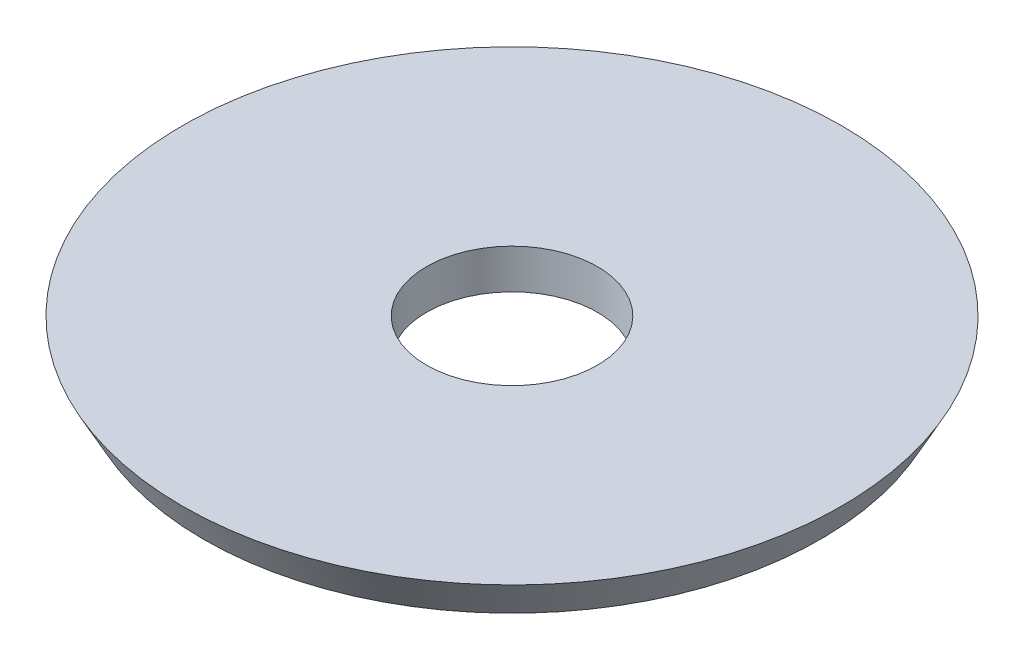
SolidWorks part; units mm, degrees
material "Epoxy, Unfilled"
ref_plane "Front Plane" through (0, 0, 0) normal (0, 0, 1) x (1, 0, 0)
ref_plane "Top Plane" through (0, 0, 0) normal (0, 1, 0) x (1, 0, 0)
ref_plane "Right Plane" through (0, 0, 0) normal (1, 0, 0) x (0, 0, -1)
sketch "Sketch1" plane through (0, 0, 0) normal (0, 1, 0) x (1, 0, 0)
  circle A0 centre (0, 0) radius 10.82
  dimension "D1" = 21.64
ref_plane "Plane1" through (0, 1.39, 0) normal (0, 1, 0) x (1, 0, 0)
sketch "Sketch2" plane through (0, 1.39, 0) normal (0, 1, 0) x (1, 0, 0)
  circle A0 centre (0, 0) radius 11.57
  dimension "D1" = 23.14
loft "Loft2" add profiles "Sketch1", "Sketch2"
sketch "Sketch9" plane through (0, 1.39, 0) normal (0, 1, 0) x (1, 0, 0)
  circle A0 centre (0, 0) radius 3
  dimension "D1" = 6
extrude "Cut-Extrude1" cut sketch "Sketch9" against normal blind 3
